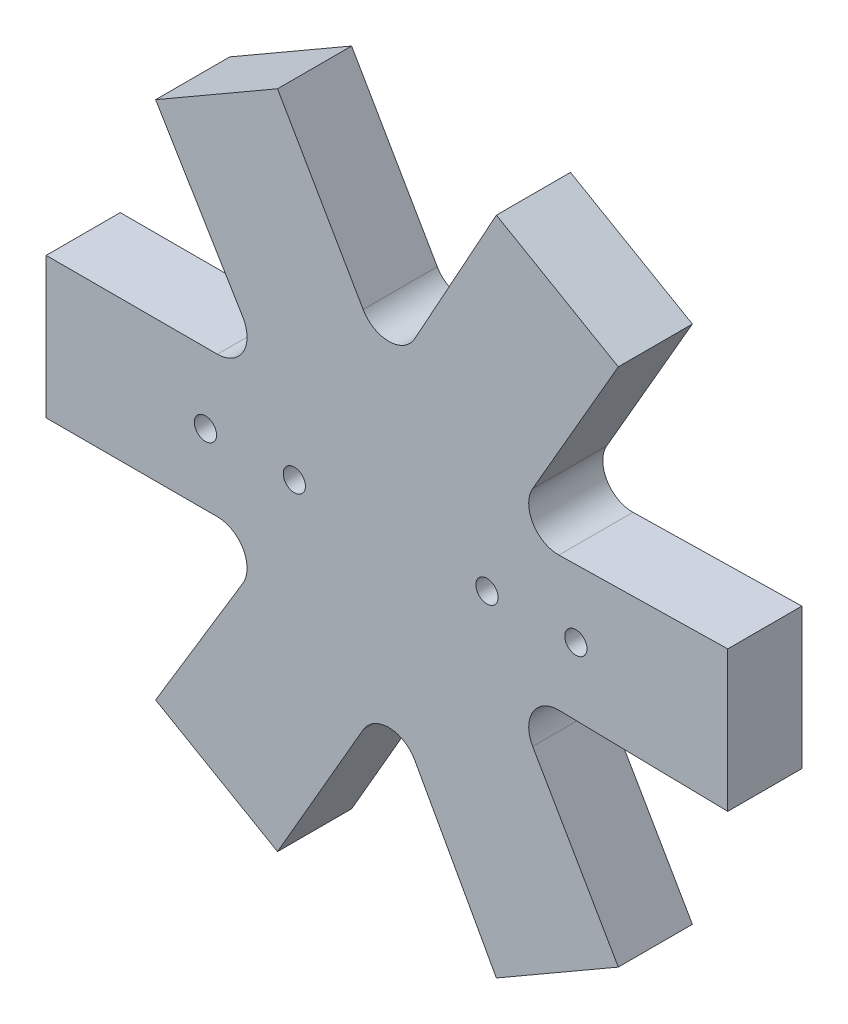
SolidWorks part; units mm, degrees
ref_plane "Front Plane" through (0, 0, 0) normal (0, 0, 1) x (1, 0, 0)
ref_plane "Top Plane" through (0, 0, 0) normal (0, 1, 0) x (1, 0, 0)
ref_plane "Right Plane" through (0, 0, 0) normal (1, 0, 0) x (0, 0, -1)
sketch "Sketch1" plane through (0, 0, 0) normal (0, 0, 1) x (1, 0, 0)
  line L4 (-23.25, 4.75) -> (-23.25, -4.75)
  line L5 (-7.6364, 22.2936) -> (-15.8636, 17.5436)
  line L8 (15.3636, 17.5436) -> (7.1364, 22.2936)
  line L11 (22.75, -4.75) -> (22.75, 4.75)
  line L14 (7.1364, -22.2936) -> (15.3636, -17.5436)
  line L17 (-15.8636, -17.5436) -> (-7.6364, -22.2936)
  line L18 (11.3543, 4.5339) -> (22.75, 4.75)
  line L19 (9.5843, 7.5335) -> (15.3636, 17.5436)
  line L20 (9.5843, -7.5335) -> (15.3636, -17.5436)
  line L21 (11.3543, -4.5339) -> (22.75, -4.75)
  line L22 (-1.8571, -12.2835) -> (-7.6364, -22.2936)
  line L23 (1.6257, -12.3165) -> (7.1364, -22.2936)
  line L24 (-11.6913, -4.75) -> (-23.25, -4.75)
  line L25 (-9.9786, -7.7827) -> (-15.8636, -17.5436)
  line L26 (-9.9786, 7.7827) -> (-15.8636, 17.5436)
  line L27 (-11.6913, 4.75) -> (-23.25, 4.75)
  line L28 (1.6257, 12.3165) -> (7.1364, 22.2936)
  line L29 (-1.8571, 12.2835) -> (-7.6364, 22.2936)
  arc A0 (11.3543, -4.5339) -> (9.5843, -7.5335) centre (11.3163, -6.5335) ccw
  arc A1 (1.6257, -12.3165) -> (-1.8571, -12.2835) centre (-0.125, -13.2835) ccw
  arc A2 (-9.9786, -7.7827) -> (-11.6913, -4.75) centre (-11.6913, -6.75) ccw
  arc A3 (-11.6913, 4.75) -> (-9.9786, 7.7827) centre (-11.6913, 6.75) ccw
  arc A4 (-1.8571, 12.2835) -> (1.6257, 12.3165) centre (-0.125, 13.2835) ccw
  arc A5 (9.5843, 7.5335) -> (11.3543, 4.5339) centre (11.3163, 6.5335) ccw
  point P2 (0, 0)
  point P6 (0, 0)
  point P7 (0, 0)
  point P11 (0, 0)
  point P12 (0, 0)
  dimension "D1" = 2
  dimension "D2" = 9.5
  dimension "D3" = 6
  dimension "D4" = 46
extrude "Boss-Extrude2" add sketch "Sketch1" along normal blind 5
sketch "Sketch2" plane through (0, 0, 0) normal (0, 0, -1) x (-1, 0, 0)
  line L0 (0, 0) -> (0, 14.25) construction
  line L1 (0, 0) -> (14, 0) construction
  line L2 (0.7806, 4.1777) -> (12.6173, 1.966)
  line L3 (0.7806, -4.1777) -> (12.6173, -1.966)
  line L4 (-0.7806, -4.1777) -> (-12.6173, -1.966)
  line L5 (-0.7806, 4.1777) -> (-12.6173, 1.966)
  circle A0 centre (0, 0) radius 14.25 construction
  arc A1 (0.7806, 4.1777) -> (-0.7806, 4.1777) centre (0, 0) ccw
  arc A2 (12.6173, -1.966) -> (12.6173, 1.966) centre (12.25, 0) ccw
  arc A3 (0.7806, -4.1777) -> (-0.7806, -4.1777) centre (0, 0) cw
  arc A4 (-12.6173, -1.966) -> (-12.6173, 1.966) centre (-12.25, 0) cw
  dimension "D1" = 28.5
  dimension "D2" = 8.5
  dimension "D3" = 4
extrude "Cut-Extrude1" cut sketch "Sketch2" against normal blind 2
sketch "Sketch3" plane through (0, 0, 2) normal (0, 0, -1) x (-1, 0, 0)
  line L0 (0, 0) -> (-14.25, 0) construction
  line L1 (0, 0) -> (0, 4.25) construction
  arc A0 (-12.6173, 1.966) -> (-12.6173, -1.966) centre (-12.25, 0) ccw construction
  arc A1 (0.7806, 4.1777) -> (-0.7806, 4.1777) centre (0, 0) ccw construction
  circle A2 centre (-6.5, 0) radius 0.75
  circle A3 centre (-12.5, 0) radius 0.75
  circle A4 centre (6.5, 0) radius 0.75
  circle A5 centre (12.5, 0) radius 0.75
  dimension "D2" = 1.5
  dimension "D3" = 1.5
  dimension "D1" = 6.5
  dimension "D4" = 12.5
extrude "Cut-Extrude2" cut sketch "Sketch3" against normal through all
